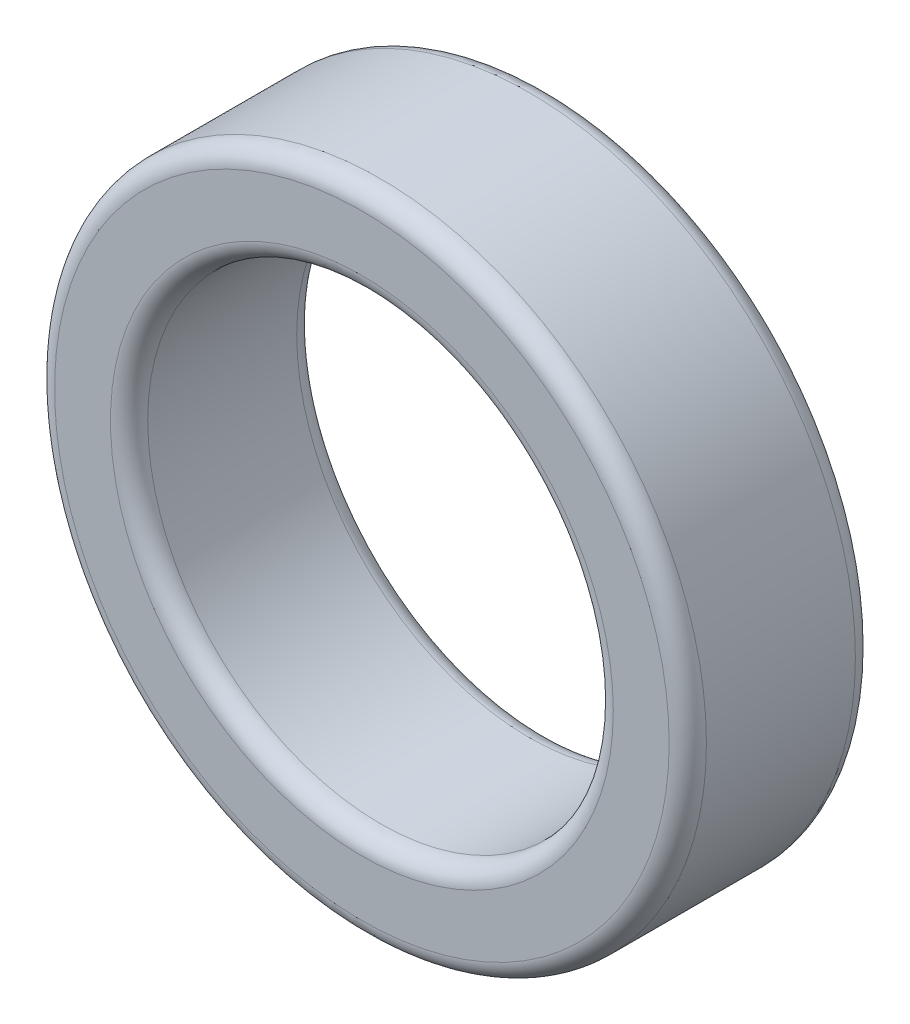
SolidWorks part; units mm, degrees
ref_plane "Front" through (0, 0, 0) normal (0, 0, 1) x (1, 0, 0)
ref_plane "Top" through (0, 0, 0) normal (0, 1, 0) x (1, 0, 0)
ref_plane "Right" through (0, 0, 0) normal (1, 0, 0) x (0, 0, -1)
sketch "Çizim1" plane through (0, 0, 0) normal (0, 0, 1) x (1, 0, 0)
  circle A0 centre (0, 0) radius 25
  circle A1 centre (0, 0) radius 35
  dimension "D1" = 50
  dimension "D2" = 70
extrude "Yükseklik-Ekstrüzyon1" add sketch "Çizim1" along normal blind 20
fillet "Radyus1" radius 2 4 edges at (35, 0, 0) (25, 0, 0) (25, 0, 20) (35, 0, 20)
